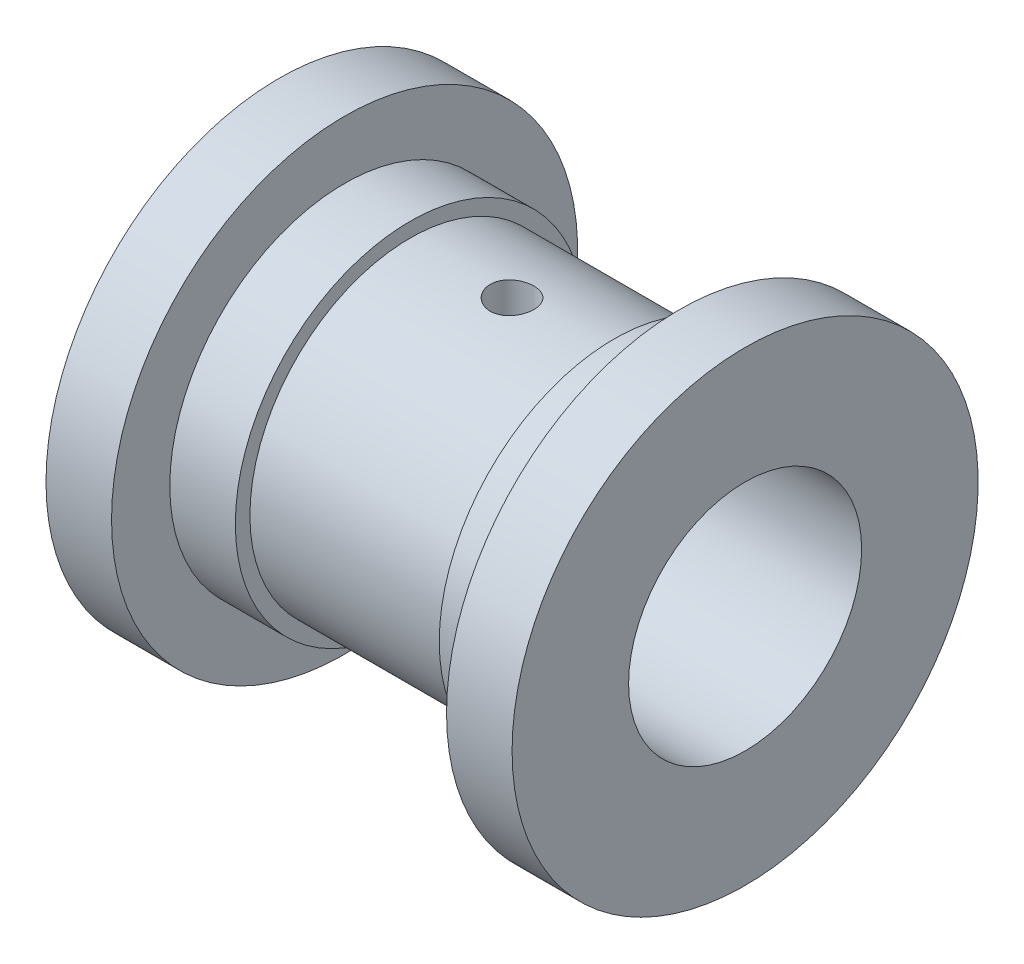
SolidWorks part; units mm, degrees
material "Phosphor bronze 10% D, UNS C52400"
ref_plane "Front Plane" through (0, 0, 0) normal (0, 0, 1) x (1, 0, 0)
ref_plane "Top Plane" through (0, 0, 0) normal (0, 1, 0) x (1, 0, 0)
ref_plane "Right Plane" through (0, 0, 0) normal (1, 0, 0) x (0, 0, -1)
sketch "Sketch1" plane through (0, 0, 0) normal (0, 0, 1) x (1, 0, 0)
  line L0 (-34.4292, 0) -> (34.4292, 0) construction
  line L1 (0, 20.4893) -> (0, -20.4893) construction
  line L2 (14, 22) -> (-14, 22)
  line L3 (-14, 22) -> (-14, 24)
  line L4 (-14, 24) -> (-23, 24)
  line L5 (-23, 24) -> (-23, 32)
  line L6 (-23, 32) -> (-32, 32)
  line L7 (-32, 32) -> (-32, 0)
  line L8 (14, 22) -> (14, 24)
  line L9 (14, 24) -> (23, 24)
  line L10 (23, 24) -> (23, 32)
  line L11 (23, 32) -> (32, 32)
  line L12 (32, 32) -> (32, 0)
  line L13 (-32, 0) -> (32, 0)
  point P4 (0, 0)
  point P8 (0, 0)
  point P16 (0, 22)
  dimension "D1" = 14
  dimension "D2" = 22
  dimension "D3" = 24
  dimension "D4" = 9
  dimension "D5" = 23
  dimension "D6" = 32
revolve "Revolve1" add sketch "Sketch1" angle 360 about L0
sketch "Sketch2" plane through (0, 0, 0) normal (0, 1, 0) x (1, 0, 0)
  circle A0 centre (0, 0) radius 4
  dimension "D1" = 8
extrude "Boss-Extrude1" add sketch "Sketch2" against normal blind 30
sketch "Sketch3" plane through (32, 0, 0) normal (1, 0, 0) x (0, 0, -1)
  circle A0 centre (0, 0) radius 16
  dimension "D1" = 32
extrude "Cut-Extrude1" cut sketch "Sketch3" against normal up to surface (64 mm away) up to face at (-32, 0, 32)
sketch "Sketch4" plane through (0, -30, 0) normal (0, -1, 0) x (1, 0, 0)
  circle A0 centre (0, 0) radius 3
  dimension "D1" = 6
extrude "Cut-Extrude2" cut sketch "Sketch4" against normal through all
